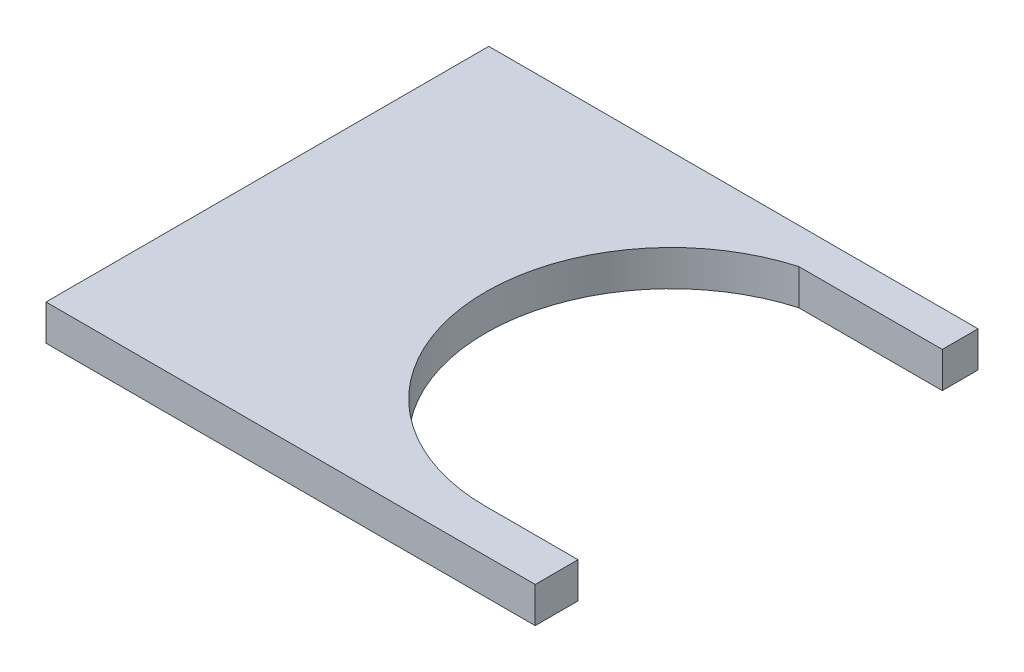
SolidWorks part; units mm, degrees
ref_plane "Front Plane" through (0, 0, 0) normal (0, 0, 1) x (1, 0, 0)
ref_plane "Top Plane" through (0, 0, 0) normal (0, 1, 0) x (1, 0, 0)
ref_plane "Right Plane" through (0, 0, 0) normal (1, 0, 0) x (0, 0, -1)
sketch "Sketch1" plane through (0, 0, 0) normal (0, 1, 0) x (1, 0, 0)
  line L0 (137, 124) -> (0, 124)
  line L1 (0, 124) -> (0, 0)
  line L2 (0, 0) -> (137, 0)
  line L3 (111.1, 12) -> (137, 12)
  line L4 (137, 12) -> (137, 0)
  line L5 (111.1, 116) -> (137, 116)
  line L6 (137, 116) -> (137, 124)
  arc A0 (111.1, 116) -> (111.1, 12) centre (111.1, 64) ccw
  dimension "D3" = 52
  dimension "D5" = 25.9
  dimension "D1" = 124
  dimension "D2" = 8
  dimension "D4" = 137
extrude "Boss-Extrude1" add sketch "Sketch1" along normal blind 10
sketch "Sketch2" plane through (0, 10, 0) normal (0, 1, 0) x (1, 0, 0)
  line L0 (96.8171, 114) -> (96.8171, 124)
  line L1 (137, 124) -> (96.8171, 124)
  line L2 (137, 124) -> (137, 114)
  line L3 (137, 114) -> (96.8171, 114)
  arc A0 (111.1, 116) -> (111.1, 12) centre (111.1, 64) ccw construction
  point P5 (96.8171, 114)
  dimension "D1" = 10
extrude "Boss-Extrude2" add sketch "Sketch2" against normal up to surface (10 mm away) up to face at (89.775, 0, -63)
